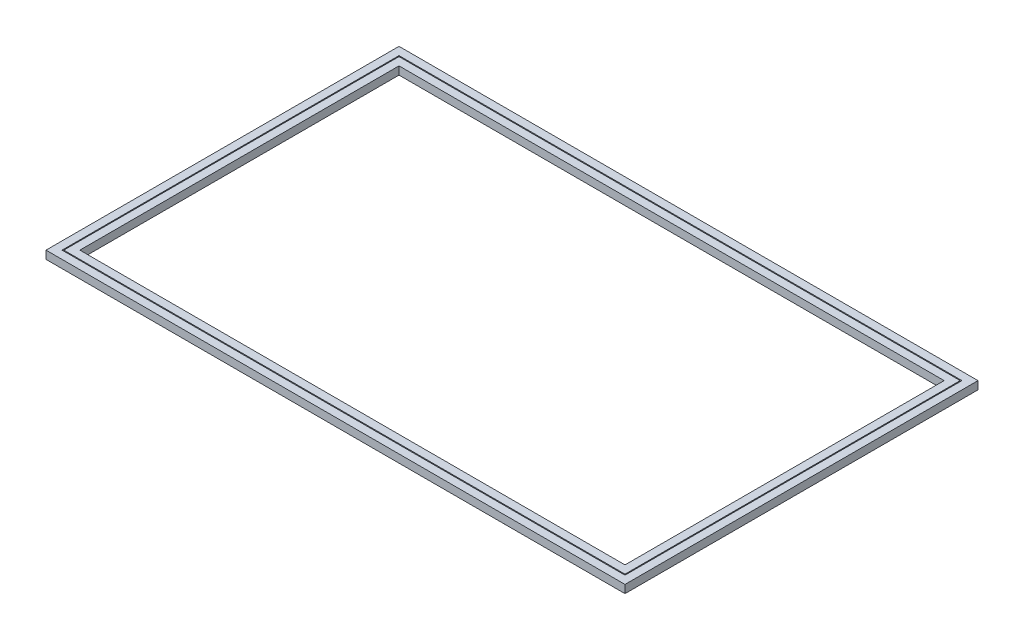
SolidWorks part; units mm, degrees
ref_plane "Front Plane" through (0, 0, 0) normal (0, 0, 1) x (1, 0, 0)
ref_plane "Top Plane" through (0, 0, 0) normal (0, 1, 0) x (1, 0, 0)
ref_plane "Right Plane" through (0, 0, 0) normal (1, 0, 0) x (0, 0, -1)
sketch "Sketch3" plane through (0, 0, 0) normal (0, 1, 0) x (1, 0, 0)
  line L0 (-315.4413, 188.6103) -> (315.4413, -188.6103) construction
  line L928 (315.4413, 188.6103) -> (-315.4413, 188.6103)
  line L939 (315.4413, -188.6103) -> (-315.4413, -188.6103)
  line L943 (-315.4413, -188.6103) -> (-315.4413, 188.6103)
  line L944 (315.4413, 188.6103) -> (315.4413, -188.6103)
sketch "Sketch6" plane through (0, 0, 0) normal (0, 1, 0) x (1, 0, 0)
  line L0 (315.9413, 0) -> (314.9413, 0) construction
  line L1 (315.9413, -189.1103) -> (-315.9413, -189.1103)
  line L2 (315.9413, -189.1103) -> (315.9413, 189.1103)
  line L3 (315.9413, 189.1103) -> (-315.9413, 189.1103)
  line L4 (-315.9413, -189.1103) -> (-315.9413, 189.1103)
  line L5 (314.9413, -188.1103) -> (-314.9413, -188.1103)
  line L6 (314.9413, -188.1103) -> (314.9413, 188.1103)
  line L7 (314.9413, 188.1103) -> (-314.9413, 188.1103)
  line L8 (-314.9413, -188.1103) -> (-314.9413, 188.1103)
  line L9 (324.9413, -198.1103) -> (-324.9413, -198.1103)
  line L10 (324.9413, -198.1103) -> (324.9413, 198.1103)
  line L11 (324.9413, 198.1103) -> (-324.9413, 198.1103)
  line L12 (-324.9413, -198.1103) -> (-324.9413, 198.1103)
  line L13 (315.4413, 188.6103) -> (315.4413, -188.6103) construction
  line L14 (0, -189.1103) -> (0, -188.1103) construction
  line L15 (315.4413, -188.6103) -> (-315.4413, -188.6103) construction
  line L16 (-314.9413, 0) -> (-315.9413, 0) construction
  line L17 (0, 189.1103) -> (0, 188.1103) construction
  line L18 (305.9413, 0) -> (314.9413, 0) construction
  line L19 (305.9413, -179.1103) -> (-305.9413, -179.1103)
  line L20 (305.9413, -179.1103) -> (305.9413, 179.1103)
  line L21 (305.9413, 179.1103) -> (-305.9413, 179.1103)
  line L22 (-305.9413, -179.1103) -> (-305.9413, 179.1103)
  line L23 (315.9413, 0) -> (324.9413, 0) construction
  line L24 (-305.9413, 0) -> (-314.9413, 0) construction
  line L25 (-315.9413, 0) -> (-324.9413, 0) construction
  line L26 (0, -179.1103) -> (0, -188.1103) construction
  line L27 (0, -198.1103) -> (0, -189.1103) construction
  line L28 (0, 179.1103) -> (0, 188.1103) construction
  line L29 (0, 198.1103) -> (0, 189.1103) construction
  point P14 (315.4413, 0)
  point P19 (0, -188.6103)
  dimension "D1" = 1
  dimension "D2" = 9
extrude "Boss-Extrude3" add sketch "Sketch6" along normal blind 9 contours L8 L5 L6 L7 L19 L22 L21 L20 | L12 L9 L10 L11 L1 L4 L3 L2
